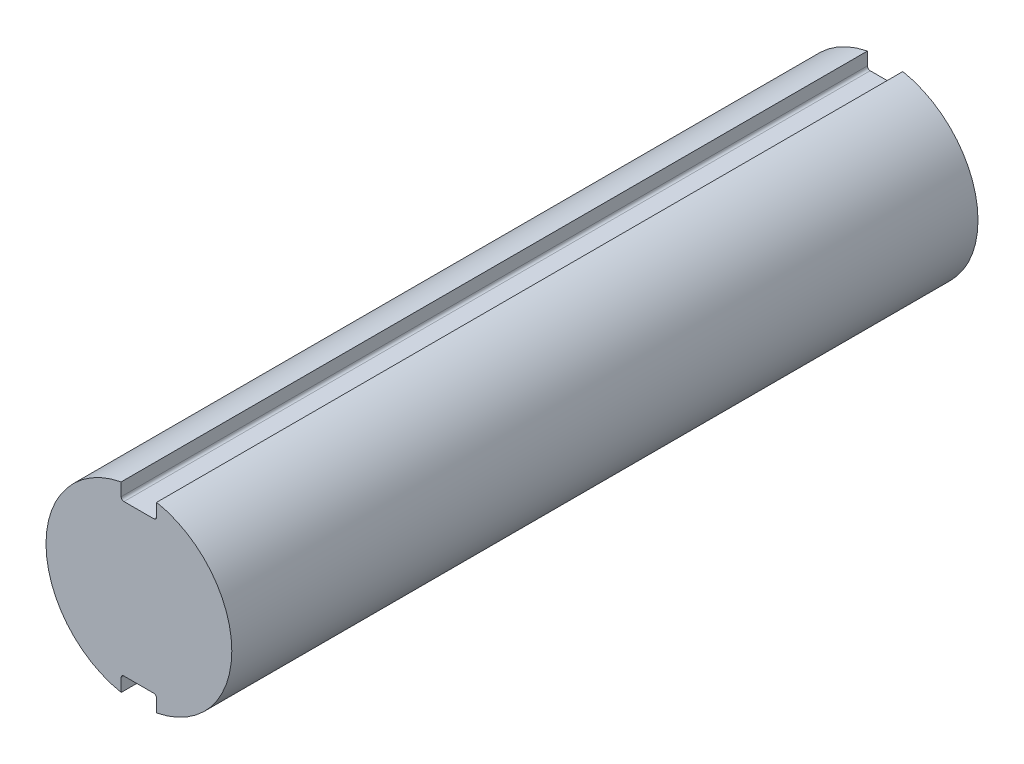
SolidWorks part; units mm, degrees
ref_plane "Ön Düzlem" through (0, 0, 0) normal (0, 0, 1) x (1, 0, 0)
ref_plane "Üst Düzlem" through (0, 0, 0) normal (0, 1, 0) x (1, 0, 0)
ref_plane "Sağ Düzlem" through (0, 0, 0) normal (1, 0, 0) x (0, 0, -1)
sketch "Model" plane through (0, 0, 0) normal (0, 0, 1) x (1, 0, 0)
  line L0 (-9.5, 79.7049) -> (9.5, 79.7049)
  line L1 (60.5945, 121.4987) -> (60.8885, 121.3363)
  line L2 (60.8885, 121.3363) -> (61.139, 121.1124)
  line L3 (61.139, 121.1124) -> (61.3334, 120.8385)
  line L4 (61.3334, 120.8385) -> (61.4619, 120.5282)
  line L5 (61.4619, 120.5282) -> (61.5182, 120.197)
  line L6 (61.5182, 120.197) -> (61.4993, 119.8617)
  line L7 (61.4993, 119.8617) -> (61.4063, 119.5389)
  line L8 (61.4063, 119.5389) -> (45.7726, 92.4605)
  line L9 (45.7726, 92.4605) -> (42.0525, 92.3778)
  line L10 (42.0525, 92.3778) -> (41.4785, 90.992)
  line L11 (58.0621, 81.4174) -> (58.9753, 82.6074)
  line L12 (58.9753, 82.6074) -> (57.1868, 85.8705)
  line L13 (57.1868, 85.8705) -> (72.8206, 112.9489)
  line L14 (72.8206, 112.9489) -> (73.0536, 113.1908)
  line L15 (73.0536, 113.1908) -> (73.3346, 113.3748)
  line L16 (73.3346, 113.3748) -> (73.6495, 113.4917)
  line L17 (73.6495, 113.4917) -> (73.9825, 113.5355)
  line L18 (73.9825, 113.5355) -> (74.317, 113.5041)
  line L19 (74.317, 113.5041) -> (74.636, 113.3991)
  line L20 (74.636, 113.3991) -> (74.9237, 113.2258)
  line L21 (74.9237, 113.2258) -> (89.976, 101.6758)
  line L22 (89.976, 101.6758) -> (90.2179, 101.4427)
  line L23 (90.2179, 101.4427) -> (90.4019, 101.1617)
  line L24 (90.4019, 101.1617) -> (90.5188, 100.8468)
  line L25 (90.5188, 100.8468) -> (90.5626, 100.5138)
  line L26 (90.5626, 100.5138) -> (90.5313, 100.1793)
  line L27 (90.5313, 100.1793) -> (90.4263, 99.8603)
  line L28 (90.4263, 99.8603) -> (90.2529, 99.5726)
  line L29 (90.2529, 99.5726) -> (68.1435, 77.4631)
  line L30 (68.1435, 77.4631) -> (64.5287, 78.3461)
  line L31 (64.5287, 78.3461) -> (63.6156, 77.1561)
  line L32 (77.1561, 63.6156) -> (78.3461, 64.5287)
  line L33 (78.3461, 64.5287) -> (77.4631, 68.1435)
  line L34 (77.4631, 68.1435) -> (99.5726, 90.2529)
  line L35 (99.5726, 90.2529) -> (99.8603, 90.4263)
  line L36 (99.8603, 90.4263) -> (100.1793, 90.5313)
  line L37 (100.1793, 90.5313) -> (100.5138, 90.5626)
  line L38 (100.5138, 90.5626) -> (100.8468, 90.5188)
  line L39 (100.8468, 90.5188) -> (101.1617, 90.4019)
  line L40 (101.1617, 90.4019) -> (101.4427, 90.2179)
  line L41 (101.4427, 90.2179) -> (101.6758, 89.976)
  line L42 (101.6758, 89.976) -> (113.2258, 74.9237)
  line L43 (113.2258, 74.9237) -> (113.3991, 74.636)
  line L44 (113.3991, 74.636) -> (113.5041, 74.317)
  line L45 (113.5041, 74.317) -> (113.5355, 73.9825)
  line L46 (113.5355, 73.9825) -> (113.4917, 73.6495)
  line L47 (113.4917, 73.6495) -> (113.3748, 73.3346)
  line L48 (113.3748, 73.3346) -> (113.1908, 73.0536)
  line L49 (113.1908, 73.0536) -> (112.9489, 72.8206)
  line L50 (112.9489, 72.8206) -> (85.8705, 57.1868)
  line L51 (85.8705, 57.1868) -> (82.6074, 58.9753)
  line L52 (82.6074, 58.9753) -> (81.4174, 58.0621)
  line L53 (90.992, 41.4785) -> (92.3778, 42.0525)
  line L54 (92.3778, 42.0525) -> (92.4605, 45.7726)
  line L55 (92.4605, 45.7726) -> (119.5389, 61.4063)
  line L56 (119.5389, 61.4063) -> (119.8617, 61.4993)
  line L57 (119.8617, 61.4993) -> (120.197, 61.5182)
  line L58 (120.197, 61.5182) -> (120.5282, 61.4619)
  line L59 (120.5282, 61.4619) -> (120.8385, 61.3334)
  line L60 (120.8385, 61.3334) -> (121.1124, 61.139)
  line L61 (121.1124, 61.139) -> (121.3363, 60.8885)
  line L62 (121.3363, 60.8885) -> (121.4987, 60.5945)
  line L63 (121.4987, 60.5945) -> (128.7594, 43.0658)
  line L64 (128.7594, 43.0658) -> (128.8524, 42.743)
  line L65 (128.8524, 42.743) -> (128.8712, 42.4076)
  line L66 (128.8712, 42.4076) -> (128.815, 42.0765)
  line L67 (128.815, 42.0765) -> (128.6864, 41.7662)
  line L68 (128.6864, 41.7662) -> (128.492, 41.4922)
  line L69 (128.492, 41.4922) -> (128.2416, 41.2684)
  line L70 (128.2416, 41.2684) -> (127.9476, 41.1059)
  line L71 (127.9476, 41.1059) -> (97.7455, 33.0133)
  line L72 (97.7455, 33.0133) -> (95.0566, 35.5853)
  line L73 (95.0566, 35.5853) -> (93.6707, 35.0113)
  line L74 (98.6269, 16.5147) -> (100.1141, 16.7105)
  line L75 (100.1141, 16.7105) -> (101.1568, 20.2824)
  line L76 (101.1568, 20.2824) -> (131.3588, 28.375)
  line L77 (131.3588, 28.375) -> (131.6947, 28.3813)
  line L78 (131.6947, 28.3813) -> (132.0235, 28.3127)
  line L79 (132.0235, 28.3127) -> (132.3288, 28.1726)
  line L80 (132.3288, 28.1726) -> (132.5953, 27.9682)
  line L81 (132.5953, 27.9682) -> (132.8096, 27.7095)
  line L82 (132.8096, 27.7095) -> (132.9609, 27.4097)
  line L83 (132.9609, 27.4097) -> (133.0418, 27.0836)
  line L84 (133.0418, 27.0836) -> (135.5183, 8.273)
  line L85 (135.5183, 8.273) -> (135.5246, 7.9371)
  line L86 (135.5246, 7.9371) -> (135.4559, 7.6083)
  line L87 (135.4559, 7.6083) -> (135.3159, 7.303)
  line L88 (135.3159, 7.303) -> (135.1114, 7.0365)
  line L89 (135.1114, 7.0365) -> (134.8528, 6.8222)
  line L90 (134.8528, 6.8222) -> (134.5529, 6.6709)
  line L91 (134.5529, 6.6709) -> (134.2269, 6.59)
  line L92 (134.2269, 6.59) -> (102.9594, 6.59)
  line L93 (102.9594, 6.59) -> (101.0278, 9.7704)
  line L94 (101.0278, 9.7704) -> (99.5406, 9.5746)
  line L95 (99.5406, -9.5746) -> (101.0278, -9.7704)
  line L96 (101.0278, -9.7704) -> (102.9594, -6.59)
  line L97 (102.9594, -6.59) -> (134.2269, -6.59)
  line L98 (134.2269, -6.59) -> (134.5529, -6.6709)
  line L99 (134.5529, -6.6709) -> (134.8528, -6.8222)
  line L100 (134.8528, -6.8222) -> (135.1114, -7.0365)
  line L101 (135.1114, -7.0365) -> (135.3159, -7.303)
  line L102 (135.3159, -7.303) -> (135.4559, -7.6083)
  line L103 (135.4559, -7.6083) -> (135.5246, -7.9371)
  line L104 (135.5246, -7.9371) -> (135.5183, -8.273)
  line L105 (135.5183, -8.273) -> (133.0418, -27.0836)
  line L106 (133.0418, -27.0836) -> (132.9609, -27.4097)
  line L107 (132.9609, -27.4097) -> (132.8096, -27.7095)
  line L108 (132.8096, -27.7095) -> (132.5953, -27.9682)
  line L109 (132.5953, -27.9682) -> (132.3288, -28.1726)
  line L110 (132.3288, -28.1726) -> (132.0235, -28.3127)
  line L111 (132.0235, -28.3127) -> (131.6947, -28.3813)
  line L112 (131.6947, -28.3813) -> (131.3588, -28.375)
  line L113 (131.3588, -28.375) -> (101.1568, -20.2824)
  line L114 (101.1568, -20.2824) -> (100.1141, -16.7105)
  line L115 (100.1141, -16.7105) -> (98.6269, -16.5147)
  line L116 (93.6707, -35.0113) -> (95.0566, -35.5853)
  line L117 (95.0566, -35.5853) -> (97.7455, -33.0133)
  line L118 (97.7455, -33.0133) -> (127.9476, -41.1059)
  line L119 (127.9476, -41.1059) -> (128.2416, -41.2684)
  line L120 (128.2416, -41.2684) -> (128.492, -41.4922)
  line L121 (128.492, -41.4922) -> (128.6864, -41.7662)
  line L122 (128.6864, -41.7662) -> (128.815, -42.0765)
  line L123 (128.815, -42.0765) -> (128.8712, -42.4076)
  line L124 (128.8712, -42.4076) -> (128.8524, -42.743)
  line L125 (128.8524, -42.743) -> (128.7594, -43.0658)
  line L126 (128.7594, -43.0658) -> (121.4987, -60.5945)
  line L127 (121.4987, -60.5945) -> (121.3363, -60.8885)
  line L128 (121.3363, -60.8885) -> (121.1124, -61.139)
  line L129 (121.1124, -61.139) -> (120.8385, -61.3334)
  line L130 (120.8385, -61.3334) -> (120.5282, -61.4619)
  line L131 (120.5282, -61.4619) -> (120.197, -61.5182)
  line L132 (120.197, -61.5182) -> (119.8617, -61.4993)
  line L133 (119.8617, -61.4993) -> (119.5389, -61.4063)
  line L134 (119.5389, -61.4063) -> (92.4605, -45.7726)
  line L135 (92.4605, -45.7726) -> (92.3778, -42.0525)
  line L136 (92.3778, -42.0525) -> (90.992, -41.4785)
  line L137 (81.4174, -58.0621) -> (82.6074, -58.9753)
  line L138 (82.6074, -58.9753) -> (85.8705, -57.1868)
  line L139 (85.8705, -57.1868) -> (112.9489, -72.8206)
  line L140 (112.9489, -72.8206) -> (113.1908, -73.0536)
  line L141 (113.1908, -73.0536) -> (113.3748, -73.3346)
  line L142 (113.3748, -73.3346) -> (113.4917, -73.6495)
  line L143 (113.4917, -73.6495) -> (113.5355, -73.9825)
  line L144 (113.5355, -73.9825) -> (113.5041, -74.317)
  line L145 (113.5041, -74.317) -> (113.3991, -74.636)
  line L146 (113.3991, -74.636) -> (113.2258, -74.9237)
  line L147 (113.2258, -74.9237) -> (101.6758, -89.976)
  line L148 (101.6758, -89.976) -> (101.4427, -90.2179)
  line L149 (101.4427, -90.2179) -> (101.1617, -90.4019)
  line L150 (101.1617, -90.4019) -> (100.8468, -90.5188)
  line L151 (100.8468, -90.5188) -> (100.5138, -90.5626)
  line L152 (100.5138, -90.5626) -> (100.1793, -90.5313)
  line L153 (100.1793, -90.5313) -> (99.8603, -90.4263)
  line L154 (99.8603, -90.4263) -> (99.5726, -90.2529)
  line L155 (99.5726, -90.2529) -> (77.4631, -68.1435)
  line L156 (77.4631, -68.1435) -> (78.3461, -64.5287)
  line L157 (78.3461, -64.5287) -> (77.1561, -63.6156)
  line L158 (63.6156, -77.1561) -> (64.5287, -78.3461)
  line L159 (64.5287, -78.3461) -> (68.1435, -77.4631)
  line L160 (68.1435, -77.4631) -> (90.2529, -99.5726)
  line L161 (90.2529, -99.5726) -> (90.4263, -99.8603)
  line L162 (90.4263, -99.8603) -> (90.5313, -100.1793)
  line L163 (90.5313, -100.1793) -> (90.5626, -100.5138)
  line L164 (90.5626, -100.5138) -> (90.5188, -100.8468)
  line L165 (90.5188, -100.8468) -> (90.4019, -101.1617)
  line L166 (90.4019, -101.1617) -> (90.2179, -101.4427)
  line L167 (90.2179, -101.4427) -> (89.976, -101.6758)
  line L168 (89.976, -101.6758) -> (74.9237, -113.2258)
  line L169 (74.9237, -113.2258) -> (74.636, -113.3991)
  line L170 (74.636, -113.3991) -> (74.317, -113.5041)
  line L171 (74.317, -113.5041) -> (73.9825, -113.5355)
  line L172 (73.9825, -113.5355) -> (73.6495, -113.4917)
  line L173 (73.6495, -113.4917) -> (73.3346, -113.3748)
  line L174 (73.3346, -113.3748) -> (73.0536, -113.1908)
  line L175 (73.0536, -113.1908) -> (72.8206, -112.9489)
  line L176 (72.8206, -112.9489) -> (57.1868, -85.8705)
  line L177 (57.1868, -85.8705) -> (58.9753, -82.6074)
  line L178 (58.9753, -82.6074) -> (58.0621, -81.4174)
  line L179 (41.4785, -90.992) -> (42.0525, -92.3778)
  line L180 (42.0525, -92.3778) -> (45.7726, -92.4605)
  line L181 (45.7726, -92.4605) -> (61.4063, -119.5389)
  line L182 (61.4063, -119.5389) -> (61.4993, -119.8617)
  line L183 (61.4993, -119.8617) -> (61.5182, -120.197)
  line L184 (61.5182, -120.197) -> (61.4619, -120.5282)
  line L185 (61.4619, -120.5282) -> (61.3334, -120.8385)
  line L186 (61.3334, -120.8385) -> (61.139, -121.1124)
  line L187 (61.139, -121.1124) -> (60.8885, -121.3363)
  line L188 (60.8885, -121.3363) -> (60.5945, -121.4987)
  line L189 (60.5945, -121.4987) -> (43.0658, -128.7594)
  line L190 (43.0658, -128.7594) -> (42.743, -128.8524)
  line L191 (42.743, -128.8524) -> (42.4076, -128.8712)
  line L192 (42.4076, -128.8712) -> (42.0765, -128.815)
  line L193 (42.0765, -128.815) -> (41.7662, -128.6864)
  line L194 (41.7662, -128.6864) -> (41.4922, -128.492)
  line L195 (41.4922, -128.492) -> (41.2684, -128.2416)
  line L196 (41.2684, -128.2416) -> (41.1059, -127.9476)
  line L197 (41.1059, -127.9476) -> (33.0133, -97.7455)
  line L198 (33.0133, -97.7455) -> (35.5853, -95.0566)
  line L199 (35.5853, -95.0566) -> (35.0113, -93.6707)
  line L200 (16.5147, -98.6269) -> (16.7105, -100.1141)
  line L201 (16.7105, -100.1141) -> (20.2824, -101.1568)
  line L202 (20.2824, -101.1568) -> (28.375, -131.3588)
  line L203 (28.375, -131.3588) -> (28.3813, -131.6947)
  line L204 (28.3813, -131.6947) -> (28.3127, -132.0235)
  line L205 (28.3127, -132.0235) -> (28.1726, -132.3288)
  line L206 (28.1726, -132.3288) -> (27.9682, -132.5953)
  line L207 (27.9682, -132.5953) -> (27.7095, -132.8096)
  line L208 (27.7095, -132.8096) -> (27.4097, -132.9609)
  line L209 (27.4097, -132.9609) -> (27.0836, -133.0418)
  line L210 (27.0836, -133.0418) -> (8.273, -135.5183)
  line L211 (8.273, -135.5183) -> (7.9371, -135.5246)
  line L212 (7.9371, -135.5246) -> (7.6083, -135.4559)
  line L213 (7.6083, -135.4559) -> (7.303, -135.3159)
  line L214 (7.303, -135.3159) -> (7.0365, -135.1114)
  line L215 (7.0365, -135.1114) -> (6.8222, -134.8528)
  line L216 (6.8222, -134.8528) -> (6.6709, -134.5529)
  line L217 (6.6709, -134.5529) -> (6.59, -134.2269)
  line L218 (6.59, -134.2269) -> (6.59, -102.9594)
  line L219 (6.59, -102.9594) -> (9.7704, -101.0278)
  line L220 (9.7704, -101.0278) -> (9.5746, -99.5406)
  line L221 (-9.5746, -99.5406) -> (-9.7704, -101.0278)
  line L222 (-9.7704, -101.0278) -> (-6.59, -102.9594)
  line L223 (-6.59, -102.9594) -> (-6.59, -134.2269)
  line L224 (-6.59, -134.2269) -> (-6.6709, -134.5529)
  line L225 (-6.6709, -134.5529) -> (-6.8222, -134.8528)
  line L226 (-6.8222, -134.8528) -> (-7.0365, -135.1114)
  line L227 (-7.0365, -135.1114) -> (-7.303, -135.3159)
  line L228 (-7.303, -135.3159) -> (-7.6083, -135.4559)
  line L229 (-7.6083, -135.4559) -> (-7.9371, -135.5246)
  line L230 (-7.9371, -135.5246) -> (-8.273, -135.5183)
  line L231 (-8.273, -135.5183) -> (-27.0836, -133.0418)
  line L232 (-27.0836, -133.0418) -> (-27.4097, -132.9609)
  line L233 (-27.4097, -132.9609) -> (-27.7095, -132.8096)
  line L234 (-27.7095, -132.8096) -> (-27.9682, -132.5953)
  line L235 (-27.9682, -132.5953) -> (-28.1726, -132.3288)
  line L236 (-28.1726, -132.3288) -> (-28.3127, -132.0235)
  line L237 (-28.3127, -132.0235) -> (-28.3813, -131.6947)
  line L238 (-28.3813, -131.6947) -> (-28.375, -131.3588)
  line L239 (-28.375, -131.3588) -> (-20.2824, -101.1568)
  line L240 (-20.2824, -101.1568) -> (-16.7105, -100.1141)
  line L241 (-16.7105, -100.1141) -> (-16.5147, -98.6269)
  line L242 (-35.0113, -93.6707) -> (-35.5853, -95.0566)
  line L243 (-35.5853, -95.0566) -> (-33.0133, -97.7455)
  line L244 (-33.0133, -97.7455) -> (-41.1059, -127.9476)
  line L245 (-41.1059, -127.9476) -> (-41.2684, -128.2416)
  line L246 (-41.2684, -128.2416) -> (-41.4922, -128.492)
  line L247 (-41.4922, -128.492) -> (-41.7662, -128.6864)
  line L248 (-41.7662, -128.6864) -> (-42.0765, -128.815)
  line L249 (-42.0765, -128.815) -> (-42.4076, -128.8712)
  line L250 (-42.4076, -128.8712) -> (-42.743, -128.8524)
  line L251 (-42.743, -128.8524) -> (-43.0658, -128.7594)
  line L252 (-43.0658, -128.7594) -> (-60.5945, -121.4987)
  line L253 (-60.5945, -121.4987) -> (-60.8885, -121.3363)
  line L254 (-60.8885, -121.3363) -> (-61.139, -121.1124)
  line L255 (-61.139, -121.1124) -> (-61.3334, -120.8385)
  line L256 (-61.3334, -120.8385) -> (-61.4619, -120.5282)
  line L257 (-61.4619, -120.5282) -> (-61.5182, -120.197)
  line L258 (-61.5182, -120.197) -> (-61.4993, -119.8617)
  line L259 (-61.4993, -119.8617) -> (-61.4063, -119.5389)
  line L260 (-61.4063, -119.5389) -> (-45.7726, -92.4605)
  line L261 (-45.7726, -92.4605) -> (-42.0525, -92.3778)
  line L262 (-42.0525, -92.3778) -> (-41.4785, -90.992)
  line L263 (-58.0621, -81.4174) -> (-58.9753, -82.6074)
  line L264 (-58.9753, -82.6074) -> (-57.1868, -85.8705)
  line L265 (-57.1868, -85.8705) -> (-72.8206, -112.9489)
  line L266 (-72.8206, -112.9489) -> (-73.0536, -113.1908)
  line L267 (-73.0536, -113.1908) -> (-73.3346, -113.3748)
  line L268 (-73.3346, -113.3748) -> (-73.6495, -113.4917)
  line L269 (-73.6495, -113.4917) -> (-73.9825, -113.5355)
  line L270 (-73.9825, -113.5355) -> (-74.317, -113.5041)
  line L271 (-74.317, -113.5041) -> (-74.636, -113.3991)
  line L272 (-74.636, -113.3991) -> (-74.9237, -113.2258)
  line L273 (-74.9237, -113.2258) -> (-89.976, -101.6758)
  line L274 (-89.976, -101.6758) -> (-90.2179, -101.4427)
  line L275 (-90.2179, -101.4427) -> (-90.4019, -101.1617)
  line L276 (-90.4019, -101.1617) -> (-90.5188, -100.8468)
  line L277 (-90.5188, -100.8468) -> (-90.5626, -100.5138)
  line L278 (-90.5626, -100.5138) -> (-90.5313, -100.1793)
  line L279 (-90.5313, -100.1793) -> (-90.4263, -99.8603)
  line L280 (-90.4263, -99.8603) -> (-90.2529, -99.5726)
  line L281 (-90.2529, -99.5726) -> (-68.1435, -77.4631)
  line L282 (-68.1435, -77.4631) -> (-64.5287, -78.3461)
  line L283 (-64.5287, -78.3461) -> (-63.6156, -77.1561)
  line L284 (-77.1561, -63.6156) -> (-78.3461, -64.5287)
  line L285 (-78.3461, -64.5287) -> (-77.4631, -68.1435)
  line L286 (-77.4631, -68.1435) -> (-99.5726, -90.2529)
  line L287 (-99.5726, -90.2529) -> (-99.8603, -90.4263)
  line L288 (-99.8603, -90.4263) -> (-100.1793, -90.5313)
  line L289 (-100.1793, -90.5313) -> (-100.5138, -90.5626)
  line L290 (-100.5138, -90.5626) -> (-100.8468, -90.5188)
  line L291 (-100.8468, -90.5188) -> (-101.1617, -90.4019)
  line L292 (-101.1617, -90.4019) -> (-101.4427, -90.2179)
  line L293 (-101.4427, -90.2179) -> (-101.6758, -89.976)
  line L294 (-101.6758, -89.976) -> (-113.2258, -74.9237)
  line L295 (-113.2258, -74.9237) -> (-113.3991, -74.636)
  line L296 (-113.3991, -74.636) -> (-113.5041, -74.317)
  line L297 (-113.5041, -74.317) -> (-113.5355, -73.9825)
  line L298 (-113.5355, -73.9825) -> (-113.4917, -73.6495)
  line L299 (-113.4917, -73.6495) -> (-113.3748, -73.3346)
  line L300 (-113.3748, -73.3346) -> (-113.1908, -73.0536)
  line L301 (-113.1908, -73.0536) -> (-112.9489, -72.8206)
  line L302 (-112.9489, -72.8206) -> (-85.8705, -57.1868)
  line L303 (-85.8705, -57.1868) -> (-82.6074, -58.9753)
  line L304 (-82.6074, -58.9753) -> (-81.4174, -58.0621)
  line L305 (-90.992, -41.4785) -> (-92.3778, -42.0525)
  line L306 (-92.3778, -42.0525) -> (-92.4605, -45.7726)
  line L307 (-92.4605, -45.7726) -> (-119.5389, -61.4063)
  line L308 (-119.5389, -61.4063) -> (-119.8617, -61.4993)
  line L309 (-119.8617, -61.4993) -> (-120.197, -61.5182)
  line L310 (-120.197, -61.5182) -> (-120.5282, -61.4619)
  line L311 (-120.5282, -61.4619) -> (-120.8385, -61.3334)
  line L312 (-120.8385, -61.3334) -> (-121.1124, -61.139)
  line L313 (-121.1124, -61.139) -> (-121.3363, -60.8885)
  line L314 (-121.3363, -60.8885) -> (-121.4987, -60.5945)
  line L315 (-121.4987, -60.5945) -> (-128.7594, -43.0658)
  line L316 (-128.7594, -43.0658) -> (-128.8524, -42.743)
  line L317 (-128.8524, -42.743) -> (-128.8712, -42.4076)
  line L318 (-128.8712, -42.4076) -> (-128.815, -42.0765)
  line L319 (-128.815, -42.0765) -> (-128.6864, -41.7662)
  line L320 (-128.6864, -41.7662) -> (-128.492, -41.4922)
  line L321 (-128.492, -41.4922) -> (-128.2416, -41.2684)
  line L322 (-128.2416, -41.2684) -> (-127.9476, -41.1059)
  line L323 (-127.9476, -41.1059) -> (-97.7455, -33.0133)
  line L324 (-97.7455, -33.0133) -> (-95.0566, -35.5853)
  line L325 (-95.0566, -35.5853) -> (-93.6707, -35.0113)
  line L326 (-98.6269, -16.5147) -> (-100.1141, -16.7105)
  line L327 (-100.1141, -16.7105) -> (-101.1568, -20.2824)
  line L328 (-101.1568, -20.2824) -> (-131.3588, -28.375)
  line L329 (-131.3588, -28.375) -> (-131.6947, -28.3813)
  line L330 (-131.6947, -28.3813) -> (-132.0235, -28.3127)
  line L331 (-132.0235, -28.3127) -> (-132.3288, -28.1726)
  line L332 (-132.3288, -28.1726) -> (-132.5953, -27.9682)
  line L333 (-132.5953, -27.9682) -> (-132.8096, -27.7095)
  line L334 (-132.8096, -27.7095) -> (-132.9609, -27.4097)
  line L335 (-132.9609, -27.4097) -> (-133.0418, -27.0836)
  line L336 (-133.0418, -27.0836) -> (-135.5183, -8.273)
  line L337 (-135.5183, -8.273) -> (-135.5246, -7.9371)
  line L338 (-135.5246, -7.9371) -> (-135.4559, -7.6083)
  line L339 (-135.4559, -7.6083) -> (-135.3159, -7.303)
  line L340 (-135.3159, -7.303) -> (-135.1114, -7.0365)
  line L341 (-135.1114, -7.0365) -> (-134.8528, -6.8222)
  line L342 (-134.8528, -6.8222) -> (-134.5529, -6.6709)
  line L343 (-134.5529, -6.6709) -> (-134.2269, -6.59)
  line L344 (-134.2269, -6.59) -> (-102.9594, -6.59)
  line L345 (-102.9594, -6.59) -> (-101.0278, -9.7704)
  line L346 (-101.0278, -9.7704) -> (-99.5406, -9.5746)
  line L347 (-99.5406, 9.5746) -> (-101.0278, 9.7704)
  line L348 (-101.0278, 9.7704) -> (-102.9594, 6.59)
  line L349 (-102.9594, 6.59) -> (-134.2269, 6.59)
  line L350 (-134.2269, 6.59) -> (-134.5529, 6.6709)
  line L351 (-134.5529, 6.6709) -> (-134.8528, 6.8222)
  line L352 (-134.8528, 6.8222) -> (-135.1114, 7.0365)
  line L353 (-135.1114, 7.0365) -> (-135.3159, 7.303)
  line L354 (-135.3159, 7.303) -> (-135.4559, 7.6083)
  line L355 (-135.4559, 7.6083) -> (-135.5246, 7.9371)
  line L356 (-135.5246, 7.9371) -> (-135.5183, 8.273)
  line L357 (-135.5183, 8.273) -> (-133.0418, 27.0836)
  line L358 (-133.0418, 27.0836) -> (-132.9609, 27.4097)
  line L359 (-132.9609, 27.4097) -> (-132.8096, 27.7095)
  line L360 (-132.8096, 27.7095) -> (-132.5953, 27.9682)
  line L361 (-132.5953, 27.9682) -> (-132.3288, 28.1726)
  line L362 (-132.3288, 28.1726) -> (-132.0235, 28.3127)
  line L363 (-132.0235, 28.3127) -> (-131.6947, 28.3813)
  line L364 (-131.6947, 28.3813) -> (-131.3588, 28.375)
  line L365 (-131.3588, 28.375) -> (-101.1568, 20.2824)
  line L366 (-101.1568, 20.2824) -> (-100.1141, 16.7105)
  line L367 (-100.1141, 16.7105) -> (-98.6269, 16.5147)
  line L368 (-93.6707, 35.0113) -> (-95.0566, 35.5853)
  line L369 (-95.0566, 35.5853) -> (-97.7455, 33.0133)
  line L370 (-97.7455, 33.0133) -> (-127.9476, 41.1059)
  line L371 (-127.9476, 41.1059) -> (-128.2416, 41.2684)
  line L372 (-128.2416, 41.2684) -> (-128.492, 41.4922)
  line L373 (-128.492, 41.4922) -> (-128.6864, 41.7662)
  line L374 (-128.6864, 41.7662) -> (-128.815, 42.0765)
  line L375 (-128.815, 42.0765) -> (-128.8712, 42.4076)
  line L376 (-128.8712, 42.4076) -> (-128.8524, 42.743)
  line L377 (-128.8524, 42.743) -> (-128.7594, 43.0658)
  line L378 (-128.7594, 43.0658) -> (-121.4987, 60.5945)
  line L379 (-121.4987, 60.5945) -> (-121.3363, 60.8885)
  line L380 (-121.3363, 60.8885) -> (-121.1124, 61.139)
  line L381 (-121.1124, 61.139) -> (-120.8385, 61.3334)
  line L382 (-120.8385, 61.3334) -> (-120.5282, 61.4619)
  line L383 (-120.5282, 61.4619) -> (-120.197, 61.5182)
  line L384 (-120.197, 61.5182) -> (-119.8617, 61.4993)
  line L385 (-119.8617, 61.4993) -> (-119.5389, 61.4063)
  line L386 (-119.5389, 61.4063) -> (-92.4605, 45.7726)
  line L387 (-92.4605, 45.7726) -> (-92.3778, 42.0525)
  line L388 (-92.3778, 42.0525) -> (-90.992, 41.4785)
  line L389 (-81.4174, 58.0621) -> (-82.6074, 58.9753)
  line L390 (-82.6074, 58.9753) -> (-85.8705, 57.1868)
  line L391 (-85.8705, 57.1868) -> (-112.9489, 72.8206)
  line L392 (-112.9489, 72.8206) -> (-113.1908, 73.0536)
  line L393 (-113.1908, 73.0536) -> (-113.3748, 73.3346)
  line L394 (-113.3748, 73.3346) -> (-113.4917, 73.6495)
  line L395 (-113.4917, 73.6495) -> (-113.5355, 73.9825)
  line L396 (-113.5355, 73.9825) -> (-113.5041, 74.317)
  line L397 (-113.5041, 74.317) -> (-113.3991, 74.636)
  line L398 (-113.3991, 74.636) -> (-113.2258, 74.9237)
  line L399 (-113.2258, 74.9237) -> (-101.6758, 89.976)
  line L400 (-101.6758, 89.976) -> (-101.4427, 90.2179)
  line L401 (-101.4427, 90.2179) -> (-101.1617, 90.4019)
  line L402 (-101.1617, 90.4019) -> (-100.8468, 90.5188)
  line L403 (-100.8468, 90.5188) -> (-100.5138, 90.5626)
  line L404 (-100.5138, 90.5626) -> (-100.1793, 90.5313)
  line L405 (-100.1793, 90.5313) -> (-99.8603, 90.4263)
  line L406 (-99.8603, 90.4263) -> (-99.5726, 90.2529)
  line L407 (-99.5726, 90.2529) -> (-77.4631, 68.1435)
  line L408 (-77.4631, 68.1435) -> (-78.3461, 64.5287)
  line L409 (-78.3461, 64.5287) -> (-77.1561, 63.6156)
  line L410 (-63.6156, 77.1561) -> (-64.5287, 78.3461)
  line L411 (-64.5287, 78.3461) -> (-68.1435, 77.4631)
  line L412 (-68.1435, 77.4631) -> (-90.2529, 99.5726)
  line L413 (-90.2529, 99.5726) -> (-90.4263, 99.8603)
  line L414 (-90.4263, 99.8603) -> (-90.5313, 100.1793)
  line L415 (-90.5313, 100.1793) -> (-90.5626, 100.5138)
  line L416 (-90.5626, 100.5138) -> (-90.5188, 100.8468)
  line L417 (-90.5188, 100.8468) -> (-90.4019, 101.1617)
  line L418 (-90.4019, 101.1617) -> (-90.2179, 101.4427)
  line L419 (-90.2179, 101.4427) -> (-89.976, 101.6758)
  line L420 (-89.976, 101.6758) -> (-74.9237, 113.2258)
  line L421 (-74.9237, 113.2258) -> (-74.636, 113.3991)
  line L422 (-74.636, 113.3991) -> (-74.317, 113.5041)
  line L423 (-74.317, 113.5041) -> (-73.9825, 113.5355)
  line L424 (-73.9825, 113.5355) -> (-73.6495, 113.4917)
  line L425 (-73.6495, 113.4917) -> (-73.3346, 113.3748)
  line L426 (-73.3346, 113.3748) -> (-73.0536, 113.1908)
  line L427 (-73.0536, 113.1908) -> (-72.8206, 112.9489)
  line L428 (-72.8206, 112.9489) -> (-57.1868, 85.8705)
  line L429 (-57.1868, 85.8705) -> (-58.9753, 82.6074)
  line L430 (-58.9753, 82.6074) -> (-58.0621, 81.4174)
  line L431 (-41.4785, 90.992) -> (-42.0525, 92.3778)
  line L432 (-42.0525, 92.3778) -> (-45.7726, 92.4605)
  line L433 (-45.7726, 92.4605) -> (-61.4063, 119.5389)
  line L434 (-61.4063, 119.5389) -> (-61.4993, 119.8617)
  line L435 (-61.4993, 119.8617) -> (-61.5182, 120.197)
  line L436 (-61.5182, 120.197) -> (-61.4619, 120.5282)
  line L437 (-61.4619, 120.5282) -> (-61.3334, 120.8385)
  line L438 (-61.3334, 120.8385) -> (-61.139, 121.1124)
  line L439 (-61.139, 121.1124) -> (-60.8885, 121.3363)
  line L440 (-60.8885, 121.3363) -> (-60.5945, 121.4987)
  line L441 (-60.5945, 121.4987) -> (-43.0658, 128.7594)
  line L442 (-43.0658, 128.7594) -> (-42.743, 128.8524)
  line L443 (-42.743, 128.8524) -> (-42.4076, 128.8712)
  line L444 (-42.4076, 128.8712) -> (-42.0765, 128.815)
  line L445 (-42.0765, 128.815) -> (-41.7662, 128.6864)
  line L446 (-41.7662, 128.6864) -> (-41.4922, 128.492)
  line L447 (-41.4922, 128.492) -> (-41.2684, 128.2416)
  line L448 (-41.2684, 128.2416) -> (-41.1059, 127.9476)
  line L449 (-41.1059, 127.9476) -> (-33.0133, 97.7455)
  line L450 (-33.0133, 97.7455) -> (-35.5853, 95.0566)
  line L451 (-35.5853, 95.0566) -> (-35.0113, 93.6707)
  line L452 (-16.5147, 98.6269) -> (-16.7105, 100.1141)
  line L453 (-16.7105, 100.1141) -> (-20.2824, 101.1568)
  line L454 (-20.2824, 101.1568) -> (-28.375, 131.3588)
  line L455 (-28.375, 131.3588) -> (-28.3813, 131.6947)
  line L456 (-28.3813, 131.6947) -> (-28.3127, 132.0235)
  line L457 (-28.3127, 132.0235) -> (-28.1726, 132.3288)
  line L458 (-28.1726, 132.3288) -> (-27.9682, 132.5953)
  line L459 (-27.9682, 132.5953) -> (-27.7095, 132.8096)
  line L460 (-27.7095, 132.8096) -> (-27.4097, 132.9609)
  line L461 (-27.4097, 132.9609) -> (-27.0836, 133.0418)
  line L462 (-27.0836, 133.0418) -> (-8.273, 135.5183)
  line L463 (-8.273, 135.5183) -> (-7.9371, 135.5246)
  line L464 (-7.9371, 135.5246) -> (-7.6083, 135.4559)
  line L465 (-7.6083, 135.4559) -> (-7.303, 135.3159)
  line L466 (-7.303, 135.3159) -> (-7.0365, 135.1114)
  line L467 (-7.0365, 135.1114) -> (-6.8222, 134.8528)
  line L468 (-6.8222, 134.8528) -> (-6.6709, 134.5529)
  line L469 (-6.6709, 134.5529) -> (-6.59, 134.2269)
  line L470 (-6.59, 134.2269) -> (-6.59, 102.9594)
  line L471 (-6.59, 102.9594) -> (-9.7704, 101.0278)
  line L472 (-9.7704, 101.0278) -> (-9.5746, 99.5406)
  line L473 (9.5746, 99.5406) -> (9.7704, 101.0278)
  line L474 (9.7704, 101.0278) -> (6.59, 102.9594)
  line L475 (6.59, 102.9594) -> (6.59, 134.2269)
  line L476 (6.59, 134.2269) -> (6.6709, 134.5529)
  line L477 (6.6709, 134.5529) -> (6.8222, 134.8528)
  line L478 (6.8222, 134.8528) -> (7.0365, 135.1114)
  line L479 (7.0365, 135.1114) -> (7.303, 135.3159)
  line L480 (7.303, 135.3159) -> (7.6083, 135.4559)
  line L481 (7.6083, 135.4559) -> (7.9371, 135.5246)
  line L482 (7.9371, 135.5246) -> (8.273, 135.5183)
  line L483 (8.273, 135.5183) -> (27.0836, 133.0418)
  line L484 (27.0836, 133.0418) -> (27.4097, 132.9609)
  line L485 (27.4097, 132.9609) -> (27.7095, 132.8096)
  line L486 (27.7095, 132.8096) -> (27.9682, 132.5953)
  line L487 (27.9682, 132.5953) -> (28.1726, 132.3288)
  line L488 (28.1726, 132.3288) -> (28.3127, 132.0235)
  line L489 (28.3127, 132.0235) -> (28.3813, 131.6947)
  line L490 (28.3813, 131.6947) -> (28.375, 131.3588)
  line L491 (28.375, 131.3588) -> (20.2824, 101.1568)
  line L492 (20.2824, 101.1568) -> (16.7105, 100.1141)
  line L493 (16.7105, 100.1141) -> (16.5147, 98.6269)
  line L494 (35.0113, 93.6707) -> (35.5853, 95.0566)
  line L495 (35.5853, 95.0566) -> (33.0133, 97.7455)
  line L496 (33.0133, 97.7455) -> (41.1059, 127.9476)
  line L497 (41.1059, 127.9476) -> (41.2684, 128.2416)
  line L498 (41.2684, 128.2416) -> (41.4922, 128.492)
  line L499 (41.4922, 128.492) -> (41.7662, 128.6864)
  line L500 (41.7662, 128.6864) -> (42.0765, 128.815)
  line L501 (42.0765, 128.815) -> (42.4076, 128.8712)
  line L502 (42.4076, 128.8712) -> (42.743, 128.8524)
  line L503 (42.743, 128.8524) -> (43.0658, 128.7594)
  line L504 (43.0658, 128.7594) -> (60.5945, 121.4987)
  line L505 (-9.5, 80.2049) -> (9.5, 80.2049)
  line L506 (10.5, 80.7049) -> (10.5, 83.8451)
  line L507 (10.5, -80.7049) -> (10.5, -83.8451)
  line L508 (27.7776, -94.5021) -> (26.5086, -90.1848)
  line L509 (2.6574, -93.9624) -> (2.7847, -98.4606)
  line L510 (-27.7776, 94.5021) -> (-26.5086, 90.1848)
  line L511 (-2.6574, 93.9624) -> (-2.7847, 98.4606)
  line L512 (94.5021, 27.7776) -> (90.1848, 26.5086)
  line L513 (93.9624, 2.6574) -> (98.4606, 2.7847)
  line L514 (-94.5021, -27.7776) -> (-90.1848, -26.5086)
  line L515 (-93.9624, -2.6574) -> (-98.4606, -2.7847)
  line L516 (55.6209, -81.2931) -> (53.0798, -77.5792)
  line L517 (31.5634, -88.5424) -> (33.0744, -92.7811)
  line L518 (-55.6209, 81.2931) -> (-53.0798, 77.5792)
  line L519 (-31.5634, 88.5424) -> (-33.0744, 92.7811)
  line L520 (81.2931, 55.6209) -> (77.5792, 53.0798)
  line L521 (88.5424, 31.5634) -> (92.7811, 33.0744)
  line L522 (-81.2931, -55.6209) -> (-77.5792, -53.0798)
  line L523 (-88.5424, -31.5634) -> (-92.7811, -33.0744)
  line L524 (78.0195, -60.1265) -> (74.4552, -57.3796)
  line L525 (57.3796, -74.4552) -> (60.1265, -78.0195)
  line L526 (-78.0195, 60.1265) -> (-74.4552, 57.3796)
  line L527 (-57.3796, 74.4552) -> (-60.1265, 78.0195)
  line L528 (60.1265, 78.0195) -> (57.3796, 74.4552)
  line L529 (74.4552, 57.3796) -> (78.0195, 60.1265)
  line L530 (-60.1265, -78.0195) -> (-57.3796, -74.4552)
  line L531 (-74.4552, -57.3796) -> (-78.0195, -60.1265)
  line L532 (92.7811, -33.0744) -> (88.5424, -31.5634)
  line L533 (77.5792, -53.0798) -> (81.2931, -55.6209)
  line L534 (-92.7811, 33.0744) -> (-88.5424, 31.5634)
  line L535 (-77.5792, 53.0798) -> (-81.2931, 55.6209)
  line L536 (33.0744, 92.7811) -> (31.5634, 88.5424)
  line L537 (53.0798, 77.5792) -> (55.6209, 81.2931)
  line L538 (-33.0744, -92.7811) -> (-31.5634, -88.5424)
  line L539 (-53.0798, -77.5792) -> (-55.6209, -81.2931)
  line L540 (98.4606, -2.7847) -> (93.9624, -2.6574)
  line L541 (90.1848, -26.5086) -> (94.5021, -27.7776)
  line L542 (-98.4606, 2.7847) -> (-93.9624, 2.6574)
  line L543 (-90.1848, 26.5086) -> (-94.5021, 27.7776)
  line L544 (2.7847, 98.4606) -> (2.6574, 93.9624)
  line L545 (26.5086, 90.1848) -> (27.7776, 94.5021)
  line L546 (-2.7847, -98.4606) -> (-2.6574, -93.9624)
  line L547 (-26.5086, -90.1848) -> (-27.7776, -94.5021)
  line L548 (9.5, -79.7049) -> (-9.5, -79.7049)
  line L549 (10, 80.7049) -> (10, 84.4097)
  line L550 (-10.5, -80.7049) -> (-10.5, -83.8451)
  line L551 (-10, 80.7049) -> (-10, 84.4097)
  line L552 (9.5, -80.2049) -> (-9.5, -80.2049)
  line L553 (-10, -80.7049) -> (-10, -84.4097)
  line L554 (10, -80.7049) -> (10, -84.4097)
  line L555 (-10.5, 80.7049) -> (-10.5, 83.8451)
  line L556 (-7.7629, 39.0257) -> (-11.9363, 62.6943)
  line L557 (7.7629, 39.0257) -> (11.9363, 62.6943)
  line L558 (16.6584, 36.1354) -> (27.1941, 57.7368)
  line L559 (29.2191, 27.0095) -> (46.5075, 43.7048)
  line L560 (22.4686, 27.2158) -> (18.9406, 29.779)
  line L561 (34.7168, 19.4426) -> (55.9373, 30.7257)
  line L562 (39.5145, 4.6766) -> (63.3144, 8.0215)
  line L563 (34.1745, 8.8113) -> (32.8269, 12.9587)
  line L564 (39.5145, -4.6766) -> (63.3144, -8.0215)
  line L565 (34.7168, -19.4426) -> (55.9373, -30.7257)
  line L566 (32.8269, -12.9587) -> (34.1745, -8.8113)
  line L567 (29.2191, -27.0095) -> (46.5075, -43.7048)
  line L568 (16.6584, -36.1354) -> (27.1941, -57.7368)
  line L569 (18.9406, -29.779) -> (22.4686, -27.2158)
  line L570 (7.7629, -39.0257) -> (11.9363, -62.6943)
  line L571 (-7.7629, -39.0257) -> (-11.9363, -62.6943)
  line L572 (-2.1804, -35.2247) -> (2.1804, -35.2247)
  line L573 (-16.6584, -36.1354) -> (-27.1941, -57.7368)
  line L574 (-29.2191, -27.0095) -> (-46.5075, -43.7048)
  line L575 (-22.4686, -27.2158) -> (-18.9406, -29.779)
  line L576 (0, -20.25) -> (4, -20.25)
  line L577 (0, -20.25) -> (-4, -20.25)
  line L578 (-34.7168, -19.4426) -> (-55.9373, -30.7257)
  line L579 (-39.5145, -4.6766) -> (-63.3144, -8.0215)
  line L580 (2.1804, 35.2247) -> (-2.1804, 35.2247)
  line L581 (-34.1745, -8.8113) -> (-32.8269, -12.9587)
  line L582 (-39.5145, 4.6766) -> (-63.3144, 8.0215)
  line L583 (-34.7168, 19.4426) -> (-55.9373, 30.7257)
  line L584 (-32.8269, 12.9587) -> (-34.1745, 8.8113)
  line L585 (-29.2191, 27.0095) -> (-46.5075, 43.7048)
  line L586 (-16.6584, 36.1354) -> (-27.1941, 57.7368)
  line L587 (-18.9406, 29.779) -> (-22.4686, 27.2158)
  line L588 (0, 20.25) -> (-4, 20.25)
  line L589 (0, 20.25) -> (4, 20.25)
  line L590 (-4.75, -21) -> (-4.75, -24.4427)
  line L591 (4.75, -21) -> (4.75, -24.4427)
  line L594 (4.75, 21) -> (4.75, 24.4427)
  line L597 (-4.75, 21) -> (-4.75, 24.4427)
  arc A0 (145, 0) -> (64.7137, 129.758) centre (0, 0) ccw
  arc A1 (58.0621, 81.4174) -> (41.4785, 90.992) centre (0, 0) ccw
  arc A2 (77.1561, 63.6156) -> (63.6156, 77.1561) centre (0, 0) ccw
  arc A3 (90.992, 41.4785) -> (81.4174, 58.0621) centre (0, 0) ccw
  arc A4 (98.6269, 16.5147) -> (93.6707, 35.0113) centre (0, 0) ccw
  arc A5 (99.5406, -9.5746) -> (99.5406, 9.5746) centre (0, 0) ccw
  arc A6 (93.6707, -35.0113) -> (98.6269, -16.5147) centre (0, 0) ccw
  arc A7 (81.4174, -58.0621) -> (90.992, -41.4785) centre (0, 0) ccw
  arc A8 (63.6156, -77.1561) -> (77.1561, -63.6156) centre (0, 0) ccw
  arc A9 (41.4785, -90.992) -> (58.0621, -81.4174) centre (0, 0) ccw
  arc A10 (16.5147, -98.6269) -> (35.0113, -93.6707) centre (0, 0) ccw
  arc A11 (-9.5746, -99.5406) -> (9.5746, -99.5406) centre (0, 0) ccw
  arc A12 (-35.0113, -93.6707) -> (-16.5147, -98.6269) centre (0, 0) ccw
  arc A13 (-58.0621, -81.4174) -> (-41.4785, -90.992) centre (0, 0) ccw
  arc A14 (-77.1561, -63.6156) -> (-63.6156, -77.1561) centre (0, 0) ccw
  arc A15 (-90.992, -41.4785) -> (-81.4174, -58.0621) centre (0, 0) ccw
  arc A16 (-98.6269, -16.5147) -> (-93.6707, -35.0113) centre (0, 0) ccw
  arc A17 (-99.5406, 9.5746) -> (-99.5406, -9.5746) centre (0, 0) ccw
  arc A18 (-93.6707, 35.0113) -> (-98.6269, 16.5147) centre (0, 0) ccw
  arc A19 (-81.4174, 58.0621) -> (-90.992, 41.4785) centre (0, 0) ccw
  arc A20 (-63.6156, 77.1561) -> (-77.1561, 63.6156) centre (0, 0) ccw
  arc A21 (-41.4785, 90.992) -> (-58.0621, 81.4174) centre (0, 0) ccw
  arc A22 (-16.5147, 98.6269) -> (-35.0113, 93.6707) centre (0, 0) ccw
  arc A23 (9.5746, 99.5406) -> (-9.5746, 99.5406) centre (0, 0) ccw
  arc A24 (35.0113, 93.6707) -> (16.5147, 98.6269) centre (0, 0) ccw
  arc A25 (64.7137, 129.758) -> (145, 0) centre (0, 0) ccw
  arc A26 (94, 0) -> (-94, 0) centre (0, 0) ccw
  arc A27 (-10, 84.4097) -> (-10, -84.4097) centre (0, 0) ccw
  arc A28 (-94, 0) -> (94, 0) centre (0, 0) ccw
  arc A29 (2.7847, -98.4606) -> (27.7776, -94.5021) centre (0, 0) ccw
  arc A30 (2.6574, -93.9624) -> (26.5086, -90.1848) centre (0, 0) ccw
  arc A31 (-2.7847, 98.4606) -> (-27.7776, 94.5021) centre (0, 0) ccw
  arc A32 (-2.6574, 93.9624) -> (-26.5086, 90.1848) centre (0, 0) ccw
  arc A33 (98.4606, 2.7847) -> (94.5021, 27.7776) centre (0, 0) ccw
  arc A34 (93.9624, 2.6574) -> (90.1848, 26.5086) centre (0, 0) ccw
  arc A35 (-98.4606, -2.7847) -> (-94.5021, -27.7776) centre (0, 0) ccw
  arc A36 (-93.9624, -2.6574) -> (-90.1848, -26.5086) centre (0, 0) ccw
  arc A37 (33.0744, -92.7811) -> (55.6209, -81.2931) centre (0, 0) ccw
  arc A38 (31.5634, -88.5424) -> (53.0798, -77.5792) centre (0, 0) ccw
  arc A39 (-33.0744, 92.7811) -> (-55.6209, 81.2931) centre (0, 0) ccw
  arc A40 (-31.5634, 88.5424) -> (-53.0798, 77.5792) centre (0, 0) ccw
  arc A41 (92.7811, 33.0744) -> (81.2931, 55.6209) centre (0, 0) ccw
  arc A42 (88.5424, 31.5634) -> (77.5792, 53.0798) centre (0, 0) ccw
  arc A43 (-92.7811, -33.0744) -> (-81.2931, -55.6209) centre (0, 0) ccw
  arc A44 (-88.5424, -31.5634) -> (-77.5792, -53.0798) centre (0, 0) ccw
  arc A45 (60.1265, -78.0195) -> (78.0195, -60.1265) centre (0, 0) ccw
  arc A46 (57.3796, -74.4552) -> (74.4552, -57.3796) centre (0, 0) ccw
  arc A47 (-60.1265, 78.0195) -> (-78.0195, 60.1265) centre (0, 0) ccw
  arc A48 (-57.3796, 74.4552) -> (-74.4552, 57.3796) centre (0, 0) ccw
  arc A49 (78.0195, 60.1265) -> (60.1265, 78.0195) centre (0, 0) ccw
  arc A50 (74.4552, 57.3796) -> (57.3796, 74.4552) centre (0, 0) ccw
  arc A51 (-78.0195, -60.1265) -> (-60.1265, -78.0195) centre (0, 0) ccw
  arc A52 (-74.4552, -57.3796) -> (-57.3796, -74.4552) centre (0, 0) ccw
  arc A53 (81.2931, -55.6209) -> (92.7811, -33.0744) centre (0, 0) ccw
  arc A54 (77.5792, -53.0798) -> (88.5424, -31.5634) centre (0, 0) ccw
  arc A55 (-81.2931, 55.6209) -> (-92.7811, 33.0744) centre (0, 0) ccw
  arc A56 (-77.5792, 53.0798) -> (-88.5424, 31.5634) centre (0, 0) ccw
  arc A57 (55.6209, 81.2931) -> (33.0744, 92.7811) centre (0, 0) ccw
  arc A58 (53.0798, 77.5792) -> (31.5634, 88.5424) centre (0, 0) ccw
  arc A59 (-55.6209, -81.2931) -> (-33.0744, -92.7811) centre (0, 0) ccw
  arc A60 (-53.0798, -77.5792) -> (-31.5634, -88.5424) centre (0, 0) ccw
  arc A61 (94.5021, -27.7776) -> (98.4606, -2.7847) centre (0, 0) ccw
  arc A62 (90.1848, -26.5086) -> (93.9624, -2.6574) centre (0, 0) ccw
  arc A63 (-94.5021, 27.7776) -> (-98.4606, 2.7847) centre (0, 0) ccw
  arc A64 (-90.1848, 26.5086) -> (-93.9624, 2.6574) centre (0, 0) ccw
  arc A65 (27.7776, 94.5021) -> (2.7847, 98.4606) centre (0, 0) ccw
  arc A66 (26.5086, 90.1848) -> (2.6574, 93.9624) centre (0, 0) ccw
  arc A67 (-27.7776, -94.5021) -> (-2.7847, -98.4606) centre (0, 0) ccw
  arc A68 (-26.5086, -90.1848) -> (-2.6574, -93.9624) centre (0, 0) ccw
  arc A69 (9.5, 80.2049) -> (10, 80.7049) centre (9.5, 80.7049) ccw
  arc A70 (-10, 80.7049) -> (-9.5, 80.2049) centre (-9.5, 80.7049) ccw
  arc A71 (-9.5, -80.2049) -> (-10, -80.7049) centre (-9.5, -80.7049) ccw
  arc A72 (10, -80.7049) -> (9.5, -80.2049) centre (9.5, -80.7049) ccw
  arc A73 (10, -84.4097) -> (10, 84.4097) centre (0, 0) ccw
  arc A74 (9.5, 79.7049) -> (10.5, 80.7049) centre (9.5, 80.7049) ccw
  arc A75 (10.5, -83.8451) -> (10.5, 83.8451) centre (0, 0) ccw
  arc A76 (10.5, -80.7049) -> (9.5, -79.7049) centre (9.5, -80.7049) ccw
  arc A77 (-9.5, -79.7049) -> (-10.5, -80.7049) centre (-9.5, -80.7049) ccw
  arc A78 (-10.5, 83.8451) -> (-10.5, -83.8451) centre (0, 0) ccw
  arc A79 (-10.5, 80.7049) -> (-9.5, 79.7049) centre (-9.5, 80.7049) ccw
  arc A80 (6.5924, 69.7096) -> (-6.5924, 69.7096) centre (0, 0) ccw
  arc A81 (4.75, -21) -> (4, -20.25) centre (4, -21) ccw
  arc A82 (2.1804, 35.2247) -> (7.7629, 39.0257) centre (2.1804, 41.2247) ccw
  arc A83 (46.3076, 52.5213) -> (35.6409, 60.2711) centre (0, 0) ccw
  arc A84 (22.4686, 27.2158) -> (29.2191, 27.0095) centre (25.9953, 32.0699) ccw
  arc A85 (46.3076, 52.5213) -> (46.5075, 43.7048) centre (42.3396, 48.0208) cw
  arc A86 (27.1941, 57.7368) -> (35.6409, 60.2711) centre (32.5869, 55.1066) cw
  arc A87 (18.9406, 29.779) -> (16.6584, 36.1354) centre (22.4673, 34.6331) cw
  arc A88 (68.3349, 15.2717) -> (64.2606, 27.8112) centre (0, 0) ccw
  arc A89 (34.1745, 8.8113) -> (39.5145, 4.6766) centre (39.8808, 10.6654) ccw
  arc A90 (68.3349, 15.2717) -> (63.3144, 8.0215) centre (62.4794, 13.9631) cw
  arc A91 (55.9373, 30.7257) -> (64.2606, 27.8112) centre (58.7542, 25.4281) cw
  arc A92 (32.8269, 12.9587) -> (34.7168, 19.4426) centre (38.5332, 14.8128) cw
  arc A93 (64.2606, -27.8112) -> (68.3349, -15.2717) centre (0, 0) ccw
  arc A94 (32.8269, -12.9587) -> (34.7168, -19.4426) centre (38.5332, -14.8128) ccw
  arc A95 (64.2606, -27.8112) -> (55.9373, -30.7257) centre (58.7542, -25.4281) cw
  arc A96 (63.3144, -8.0215) -> (68.3349, -15.2717) centre (62.4794, -13.9631) cw
  arc A97 (34.1745, -8.8113) -> (39.5145, -4.6766) centre (39.8808, -10.6654) cw
  arc A98 (6.5924, 69.7096) -> (11.9363, 62.6943) centre (6.0275, 63.7362) cw
  arc A99 (35.6409, -60.2711) -> (46.3076, -52.5213) centre (0, 0) ccw
  arc A100 (18.9406, -29.779) -> (16.6584, -36.1354) centre (22.4673, -34.6331) ccw
  arc A101 (-11.9363, 62.6943) -> (-6.5924, 69.7096) centre (-6.0275, 63.7362) cw
  arc A102 (35.6409, -60.2711) -> (27.1941, -57.7368) centre (32.5869, -55.1066) cw
  arc A103 (46.5075, -43.7048) -> (46.3076, -52.5213) centre (42.3396, -48.0208) cw
  arc A104 (22.4686, -27.2158) -> (29.2191, -27.0095) centre (25.9953, -32.0699) cw
  arc A105 (-6.5924, -69.7096) -> (6.5924, -69.7096) centre (0, 0) ccw
  arc A106 (-2.1804, -35.2247) -> (-7.7629, -39.0257) centre (-2.1804, -41.2247) ccw
  arc A107 (-6.5924, -69.7096) -> (-11.9363, -62.6943) centre (-6.0275, -63.7362) cw
  arc A108 (11.9363, -62.6943) -> (6.5924, -69.7096) centre (6.0275, -63.7362) cw
  arc A109 (2.1804, -35.2247) -> (7.7629, -39.0257) centre (2.1804, -41.2247) cw
  arc A110 (-46.3076, -52.5213) -> (-35.6409, -60.2711) centre (0, 0) ccw
  arc A111 (-22.4686, -27.2158) -> (-29.2191, -27.0095) centre (-25.9953, -32.0699) ccw
  arc A112 (-46.3076, -52.5213) -> (-46.5075, -43.7048) centre (-42.3396, -48.0208) cw
  arc A113 (-27.1941, -57.7368) -> (-35.6409, -60.2711) centre (-32.5869, -55.1066) cw
  arc A114 (-18.9406, -29.779) -> (-16.6584, -36.1354) centre (-22.4673, -34.6331) cw
  arc A115 (-68.3349, -15.2717) -> (-64.2606, -27.8112) centre (0, 0) ccw
  arc A116 (-34.1745, -8.8113) -> (-39.5145, -4.6766) centre (-39.8808, -10.6654) ccw
  arc A117 (-68.3349, -15.2717) -> (-63.3144, -8.0215) centre (-62.4794, -13.9631) cw
  arc A118 (-55.9373, -30.7257) -> (-64.2606, -27.8112) centre (-58.7542, -25.4281) cw
  arc A119 (-32.8269, -12.9587) -> (-34.7168, -19.4426) centre (-38.5332, -14.8128) cw
  arc A120 (-64.2606, 27.8112) -> (-68.3349, 15.2717) centre (0, 0) ccw
  arc A121 (-32.8269, 12.9587) -> (-34.7168, 19.4426) centre (-38.5332, 14.8128) ccw
  arc A122 (-64.2606, 27.8112) -> (-55.9373, 30.7257) centre (-58.7542, 25.4281) cw
  arc A123 (-63.3144, 8.0215) -> (-68.3349, 15.2717) centre (-62.4794, 13.9631) cw
  arc A124 (-34.1745, 8.8113) -> (-39.5145, 4.6766) centre (-39.8808, 10.6654) cw
  arc A125 (-35.6409, 60.2711) -> (-46.3076, 52.5213) centre (0, 0) ccw
  arc A126 (-18.9406, 29.779) -> (-16.6584, 36.1354) centre (-22.4673, 34.6331) ccw
  arc A127 (-35.6409, 60.2711) -> (-27.1941, 57.7368) centre (-32.5869, 55.1066) cw
  arc A128 (-46.5075, 43.7048) -> (-46.3076, 52.5213) centre (-42.3396, 48.0208) cw
  arc A129 (-22.4686, 27.2158) -> (-29.2191, 27.0095) centre (-25.9953, 32.0699) cw
  circle A130 centre (-72.5, 0) radius 3
  circle A131 centre (-58.6537, 42.6144) radius 3
  circle A132 centre (-22.4037, 68.9516) radius 3
  circle A133 centre (22.4037, 68.9516) radius 3
  circle A134 centre (58.6537, 42.6144) radius 3
  circle A135 centre (72.5, 0) radius 3
  circle A136 centre (58.6537, -42.6144) radius 3
  circle A137 centre (22.4037, -68.9516) radius 3
  circle A138 centre (-22.4037, -68.9516) radius 3
  circle A139 centre (-58.6537, -42.6144) radius 3
  arc A140 (-4, -20.25) -> (-4.75, -21) centre (-4, -21) ccw
  arc A141 (4.75, -24.4427) -> (4.75, 24.4427) centre (0, 0) ccw
  arc A142 (-2.1804, 35.2247) -> (-7.7629, 39.0257) centre (-2.1804, 41.2247) cw
  arc A143 (-4.75, 21) -> (-4, 20.25) centre (-4, 21) ccw
  arc A144 (4, 20.25) -> (4.75, 21) centre (4, 21) ccw
  arc A146 (-4.75, 24.4427) -> (-4.75, -24.4427) centre (0, 0) ccw
  point P656 (9.8496, 50.86)
  point P657 (0, 70.0206)
  point P659 (7.0927, 35.2247)
  point P669 (26.4427, 24.3284)
  point P674 (14.9665, 32.6664)
  point P683 (35.6925, 4.1395)
  point P691 (31.3089, 17.6306)
  point P700 (31.3089, -17.6306)
  point P705 (35.6925, -4.1395)
  point P714 (14.9665, -32.6664)
  point P719 (26.4427, -24.3284)
  point P728 (-7.0927, -35.2247)
  point P733 (7.0927, -35.2247)
  point P742 (-26.4427, -24.3284)
  point P747 (-14.9665, -32.6664)
  point P756 (-35.6925, -4.1395)
  point P761 (-31.3089, -17.6306)
  point P770 (-31.3089, 17.6306)
  point P777 (-7.0927, 35.2247)
  point P779 (-35.6925, 4.1395)
  point P790 (-14.9665, 32.6664)
  point P795 (-26.4427, 24.3284)
  point P812 (0, 0)
  point P831 (0, 0)
  point P832 (0, 0)
  dimension "D3" = 2
  dimension "D2" = 10
  dimension "D4" = 6
  dimension "D5" = 2
  dimension "D1" = 0.5
extrude "Yükseklik-Ekstrüzyon3" add sketch "Model" along normal blind 200 contours L597 A146 L590 A140 L577 L576 A81 L591 A141 L594 A144 L589 L588 A143
